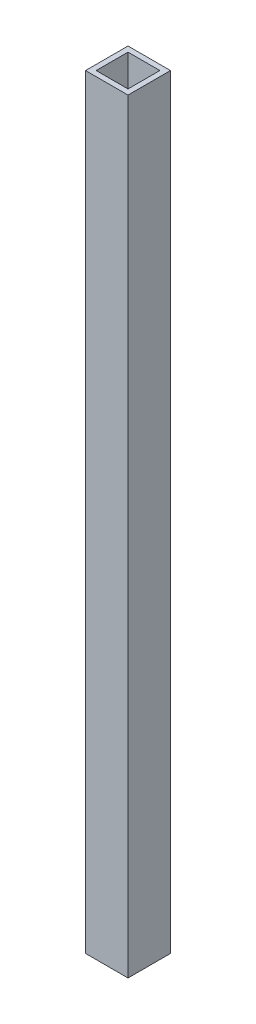
SolidWorks part; units mm, degrees
material "1060 Alloy"
ref_plane "Front Plane" through (0, 0, 0) normal (0, 0, 1) x (1, 0, 0)
ref_plane "Top Plane" through (0, 0, 0) normal (0, 1, 0) x (1, 0, 0)
ref_plane "Right Plane" through (0, 0, 0) normal (1, 0, 0) x (0, 0, -1)
sketch "Sketch1" plane through (0, 0, 0) normal (0, 1, 0) x (1, 0, 0)
  line L1 (0, 0) -> (25.4, 0)
  line L2 (0, 0) -> (0, 25.4)
  line L3 (0, 25.4) -> (25.4, 25.4)
  line L4 (25.4, 0) -> (25.4, 25.4)
  line L5 (3.175, 3.175) -> (22.225, 3.175)
  line L6 (3.175, 3.175) -> (3.175, 22.225)
  line L7 (3.175, 22.225) -> (22.225, 22.225)
  line L8 (22.225, 3.175) -> (22.225, 22.225)
  dimension "D1" = 25.4
  dimension "D2" = 25.4
  dimension "D3" = 3.175
  dimension "D4" = 3.175
  dimension "D5" = 3.175
  dimension "D6" = 3.175
extrude "Boss-Extrude1" add sketch "Sketch1" along normal blind 457.2
